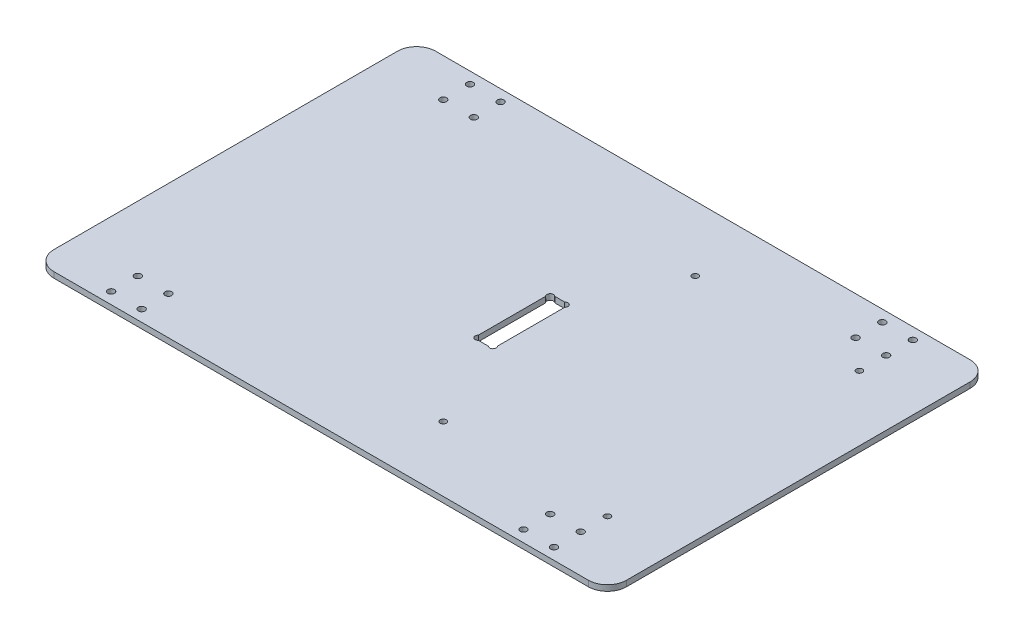
SolidWorks part; units mm, degrees
ref_plane "前视基准面" through (0, 0, 0) normal (0, 0, 1) x (1, 0, 0)
ref_plane "上视基准面" through (0, 0, 0) normal (0, 1, 0) x (1, 0, 0)
ref_plane "右视基准面" through (0, 0, 0) normal (1, 0, 0) x (0, 0, -1)
other "Configuration Table"
sketch "草图1" plane through (0, 0, 0) normal (0, 1, 0) x (1, 0, 0)
  line L1 (-140, 100) -> (140, 100)
  line L2 (-150, 90) -> (-150, -90)
  line L3 (-140, -100) -> (140, -100)
  line L4 (150, 90) -> (150, -90)
  arc A0 (-140, 100) -> (-150, 90) centre (-140, 90) ccw
  arc A1 (140, 100) -> (150, 90) centre (140, 90) cw
  arc A2 (140, -100) -> (150, -90) centre (140, -90) ccw
  arc A3 (-150, -90) -> (-140, -100) centre (-140, -90) ccw
  dimension "D5" = 10
  dimension "D6" = 10
  dimension "D7" = 10
  dimension "D1" = 150
  dimension "D2" = 150
  dimension "D3" = 100
  dimension "D4" = 100
extrude "凸台-拉伸1" add sketch "草图1" along normal blind 3
sketch "草图15" plane through (0, 3, 0) normal (0, 1, 0) x (1, 0, 0)
  line L0 (1.2, 18.8) -> (1.2, -18.8) construction
  line L5 (2.4042, 20) -> (7.5958, 20)
  line L6 (0, 17.5958) -> (0, -17.5958)
  line L7 (0, 0) -> (24.1687, 0) construction
  line L8 (2.4042, -20) -> (7.5958, -20)
  line L9 (10, 17.5958) -> (10, -17.5958)
  line L10 (1.2, -18.8) -> (8.8, -18.8) construction
  line L11 (8.8, 18.8) -> (8.8, -18.8) construction
  line L12 (1.2, 18.8) -> (8.8, 18.8) construction
  line L14 (0, 20) -> (10, 20) construction
  line L15 (0, 20) -> (0, -20) construction
  line L20 (10, 20) -> (10, -20) construction
  line L21 (0, -20) -> (10, -20) construction
  line L27 (0, 2.4042) -> (0, 44.4718) construction
  circle A11 centre (-116, 94) radius 1.75
  circle A12 centre (-100, 94) radius 1.75
  circle A13 centre (-116, 80) radius 1.75
  circle A14 centre (-100, 80) radius 1.75
  circle A15 centre (-116, -80) radius 1.75
  circle A16 centre (-100, -80) radius 1.75
  circle A17 centre (-116, -94) radius 1.75
  circle A18 centre (-100, -94) radius 1.75
  circle A19 centre (100, -80) radius 1.75
  circle A20 centre (116, -80) radius 1.75
  circle A21 centre (100, -94) radius 1.75
  circle A22 centre (100, 94) radius 1.75
  circle A23 centre (116, 94) radius 1.75
  circle A24 centre (100, 80) radius 1.75
  circle A25 centre (116, 80) radius 1.75
  circle A26 centre (116, -94) radius 1.75
  circle A27 centre (30, 66) radius 1.6
  circle A28 centre (116, 66) radius 1.6
  circle A29 centre (30, -66) radius 1.6
  circle A30 centre (116, -66) radius 1.6
  arc A31 (2.4042, 20) -> (0, 17.5958) centre (1.2, 18.8) ccw
  arc A33 (7.5958, -20) -> (10, -17.5958) centre (8.8, -18.8) ccw
  arc A35 (10, 17.5958) -> (7.5958, 20) centre (8.8, 18.8) ccw
  arc A36 (0, -17.5958) -> (2.4042, -20) centre (1.2, -18.8) ccw
  point P0 (-90.5, -9.8)
  point P1 (-80.5, -30)
  point P2 (-90.5, -30)
  point P3 (-80.5, -9.8)
  dimension "D8" = 10
  dimension "D13" = 86
  dimension "D15" = 66
  dimension "D17" = 30
  dimension "D18" = 30
  dimension "D19" = 1.2
  dimension "D21" = 3.5
  dimension "D24" = 100
  dimension "D27" = 100
  dimension "D28" = 100
  dimension "D29" = 100
  dimension "D30" = 80
  dimension "D31" = 14
  dimension "D33" = 80
  dimension "D34" = 14
  dimension "D35" = 14
  dimension "D36" = 14
  dimension "D37" = 14
  dimension "D38" = 14
  dimension "D39" = 14
  dimension "D43" = 80
  dimension "D44" = 80
  dimension "D46" = 16
  dimension "D47" = 16
  dimension "D48" = 16
  dimension "D49" = 16
  dimension "D50" = 16
  dimension "D51" = 16
  dimension "D52" = 16
  dimension "D53" = 16
  dimension "D9" = 80
  dimension "D10" = 66
  dimension "D11" = 66
  dimension "D12" = 86
  dimension "D14" = 66
  dimension "D16" = 3.2
  dimension "D20" = 3.4
  dimension "D1" = 10
  dimension "D6" = 20
  dimension "D7" = 20
  dimension "D22" = 100
  dimension "D23" = 100
  dimension "D25" = 100
  dimension "D26" = 100
  dimension "D32" = 14
  dimension "D40" = 80
  dimension "D41" = 80
  dimension "D42" = 80
extrude "切除-拉伸7" cut sketch "草图15" against normal blind 3
